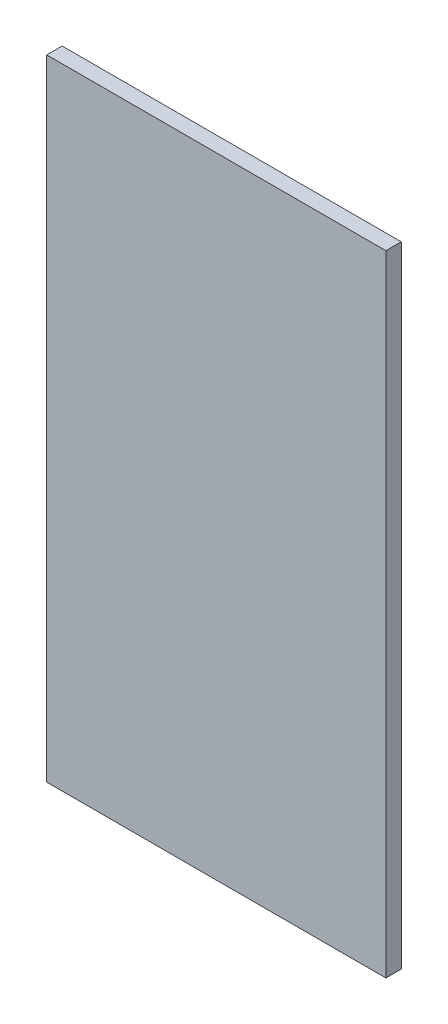
SolidWorks part; units mm, degrees
ref_plane "Front Plane" through (0, 0, 0) normal (0, 0, 1) x (1, 0, 0)
ref_plane "Top Plane" through (0, 0, 0) normal (0, 1, 0) x (1, 0, 0)
ref_plane "Right Plane" through (0, 0, 0) normal (1, 0, 0) x (0, 0, -1)
sketch "Sketch1" plane through (0, 0, 0) normal (0, 0, 1) x (1, 0, 0)
  line L1 (-50, 2.5) -> (-15, 2.5)
  line L2 (-50, 2.5) -> (-50, 67.5)
  line L3 (-50, 67.5) -> (-15, 67.5)
  line L4 (-15, 2.5) -> (-15, 67.5)
  line L5 (-50.5, 69) -> (-14.5, 69) construction
  line L6 (-50.5, 1) -> (-50.5, 69) construction
  point P7 (-32.5, 69)
  point P8 (-32.5, 67.5)
  point P11 (-50.5, 35)
  point P12 (-50, 35)
  dimension "D1" = 35
  dimension "D2" = 65
extrude "Boss-Extrude1" add sketch "Sketch1" along normal blind 1.5875
